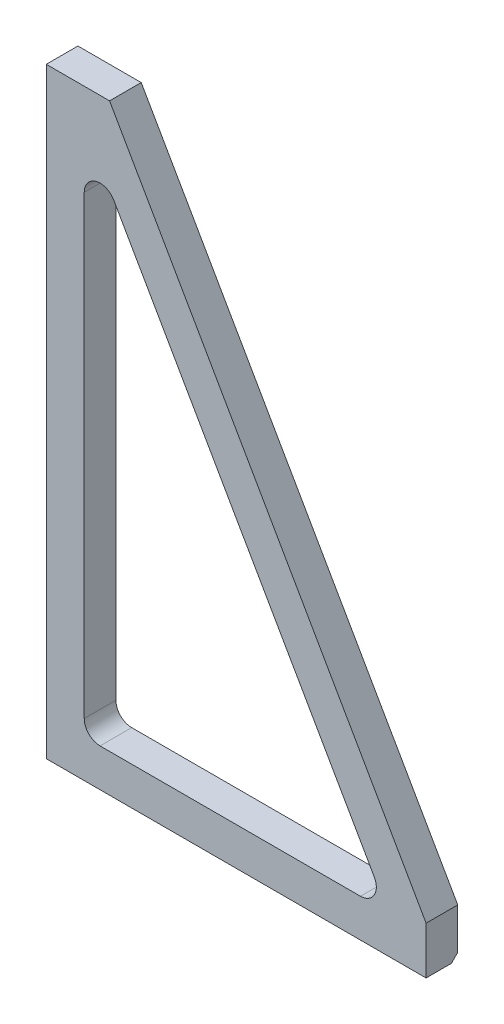
SolidWorks part; units mm, degrees
ref_plane "Front" through (0, 0, 0) normal (0, 0, 1) x (1, 0, 0)
ref_plane "Top" through (0, 0, 0) normal (0, 1, 0) x (1, 0, 0)
ref_plane "Right" through (0, 0, 0) normal (1, 0, 0) x (0, 0, -1)
other "Configuration Table"
sketch "Sketch1" plane through (0, 0, 0) normal (0, 0, 1) x (1, 0, 0)
  line L0 (15.24, 21.59) -> (15.24, 204.4515)
  line L1 (0, 0) -> (152.4, 0)
  line L2 (0, 0) -> (0, 241.3)
  line L3 (0, 241.3) -> (25.4, 241.3)
  line L4 (152.4, 0) -> (152.4, 19.05)
  line L7 (21.59, 15.24) -> (126.0823, 15.24)
  line L8 (25.4, 241.3) -> (152.4, 19.05)
  line L9 (27.1033, 207.6019) -> (131.5956, 24.7405)
  arc A0 (131.5956, 24.7405) -> (126.0823, 15.24) centre (126.0823, 21.59) cw
  arc A3 (15.24, 21.59) -> (21.59, 15.24) centre (21.59, 21.59) ccw
  arc A4 (15.24, 204.4515) -> (27.1033, 207.6019) centre (21.59, 204.4515) cw
  dimension "D4" = 6.35
  dimension "D8" = 6.35
  dimension "D9" = 6.35
  dimension "D1" = 152.4
  dimension "D2" = 241.3
  dimension "D5" = 19.05
  dimension "D6" = 25.4
  dimension "D3" = 15.24
  dimension "D7" = 15.24
extrude "Base-Extrude" add sketch "Sketch1" along normal blind 12.7
chamfer "Chamfer3" distance 2.54 angle 45 1 edges at (76.2, 0, 0)
